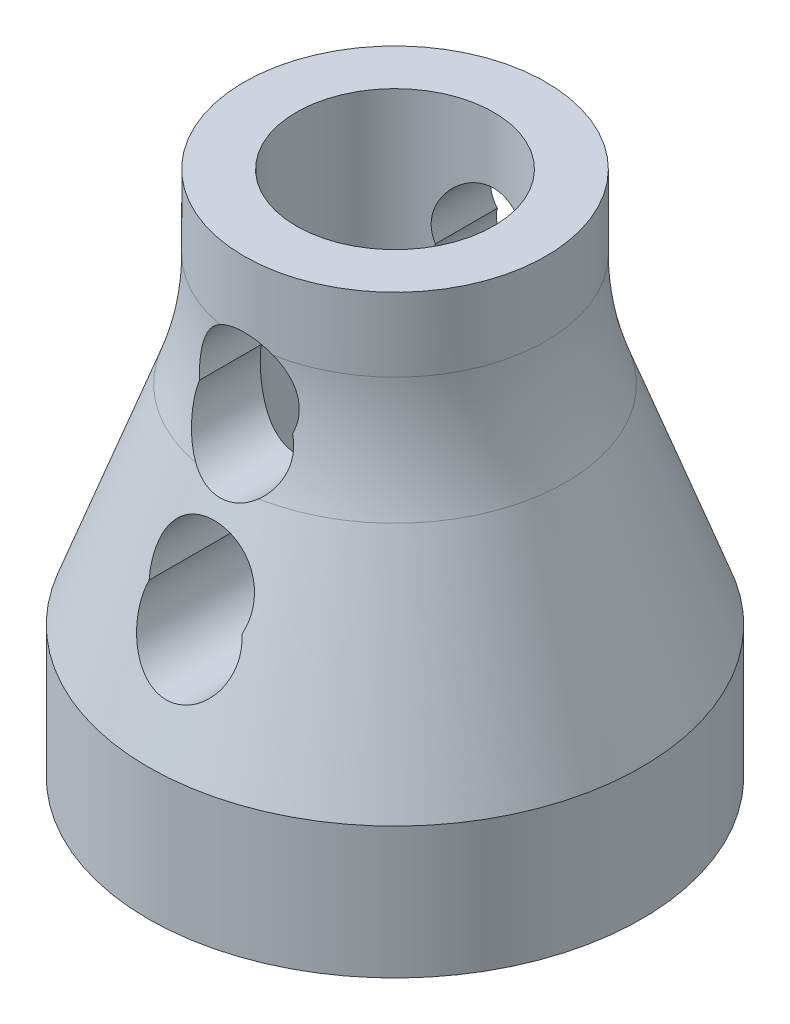
SolidWorks part; units mm, degrees
ref_plane "Front Plane" through (0, 0, 0) normal (0, 0, 1) x (1, 0, 0)
ref_plane "Top Plane" through (0, 0, 0) normal (0, 1, 0) x (1, 0, 0)
ref_plane "Right Plane" through (0, 0, 0) normal (1, 0, 0) x (0, 0, -1)
sketch "Sketch1" plane through (0, 0, 0) normal (0, 1, 0) x (1, 0, 0)
  circle A0 centre (0, 0) radius 7.5
  dimension "D1" = 15
extrude "Boss-Extrude1" add sketch "Sketch1" along normal blind 4
sketch "Sketch4" plane through (0, 4, 0) normal (0, 1, 0) x (1, 0, 0)
  circle A0 centre (0, 0) radius 7.5
extrude "Boss-Extrude4" add sketch "Sketch4" along normal blind 8 draft 20
sketch "Sketch5" plane through (0, 0, 0) normal (0, -1, 0) x (-1, 0, 0)
  circle A0 centre (0, 0) radius 1.5
  dimension "D1" = 3
extrude "Cut-Extrude2" cut sketch "Sketch5" against normal through all
sketch "Sketch6" plane through (0, 12, 0) normal (0, 1, 0) x (1, 0, 0)
  circle A0 centre (0, 0) radius 3
  dimension "D1" = 6
extrude "Cut-Extrude3" cut sketch "Sketch6" against normal blind 9
ref_plane "Plane1" through (0, 0, 10) normal (0, 0, 1) x (1, 0, 0)
sketch "Sketch7" plane through (0, 0, 10) normal (0, 0, 1) x (1, 0, 0)
  line L0 (4.5882, 12) -> (-4.5882, 12) construction
  circle A0 centre (0, 8) radius 1.5
  dimension "D1" = 3
  dimension "D2" = 4
extrude "Cut-Extrude4" cut sketch "Sketch7" against normal through all
sketch "Sketch8" plane through (0, 0, 10) normal (0, 0, 1) x (1, 0, 0)
  circle A0 centre (0, 7) radius 1.5
  circle A1 centre (0, 8) radius 1.5 construction
  dimension "D1" = 3
  dimension "D2" = 1
extrude "Cut-Extrude5" cut sketch "Sketch8" against normal through all
sketch "Sketch9" plane through (0, 12, 0) normal (0, 1, 0) x (1, 0, 0)
  circle A0 centre (0, 0) radius 3
  circle A1 centre (0, 0) radius 4.5882
extrude "Boss-Extrude5" add sketch "Sketch9" along normal blind 4
fillet "Fillet1" radius 10 1 edges at (0, 12, 4.5882)
sketch "Sketch10" plane through (0, 0, 10) normal (0, 0, 1) x (1, 0, 0)
  line L1 (7.5, 4) -> (-7.5, 4) construction
  circle A0 centre (0, 11.5) radius 1.5
  circle A1 centre (0, 12.5) radius 1.5
  dimension "D1" = 3
  dimension "D2" = 3
  dimension "D3" = 1
  dimension "D4" = 7.5
extrude "Cut-Extrude6" cut sketch "Sketch10" against normal through all contours A0 A1 | A0 A1 | A1 A0
